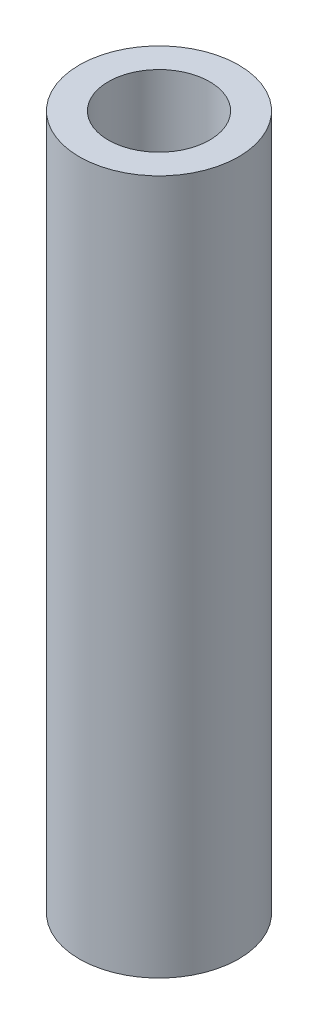
SolidWorks part; units mm, degrees
material "ABS"
ref_plane "前视基准面" through (0, 0, 0) normal (0, 0, 1) x (1, 0, 0)
ref_plane "上视基准面" through (0, 0, 0) normal (0, 1, 0) x (1, 0, 0)
ref_plane "右视基准面" through (0, 0, 0) normal (1, 0, 0) x (0, 0, -1)
other "Configuration Table"
sketch "草图1" plane through (0, 0, 0) normal (0, 1, 0) x (1, 0, 0)
  circle A0 centre (0, 0) radius 1.75
  circle A1 centre (0, 0) radius 2.75
  dimension "D1" = 3.5
  dimension "D2" = 5.5
extrude "凸台-拉伸1" add sketch "草图1" along normal blind 24
